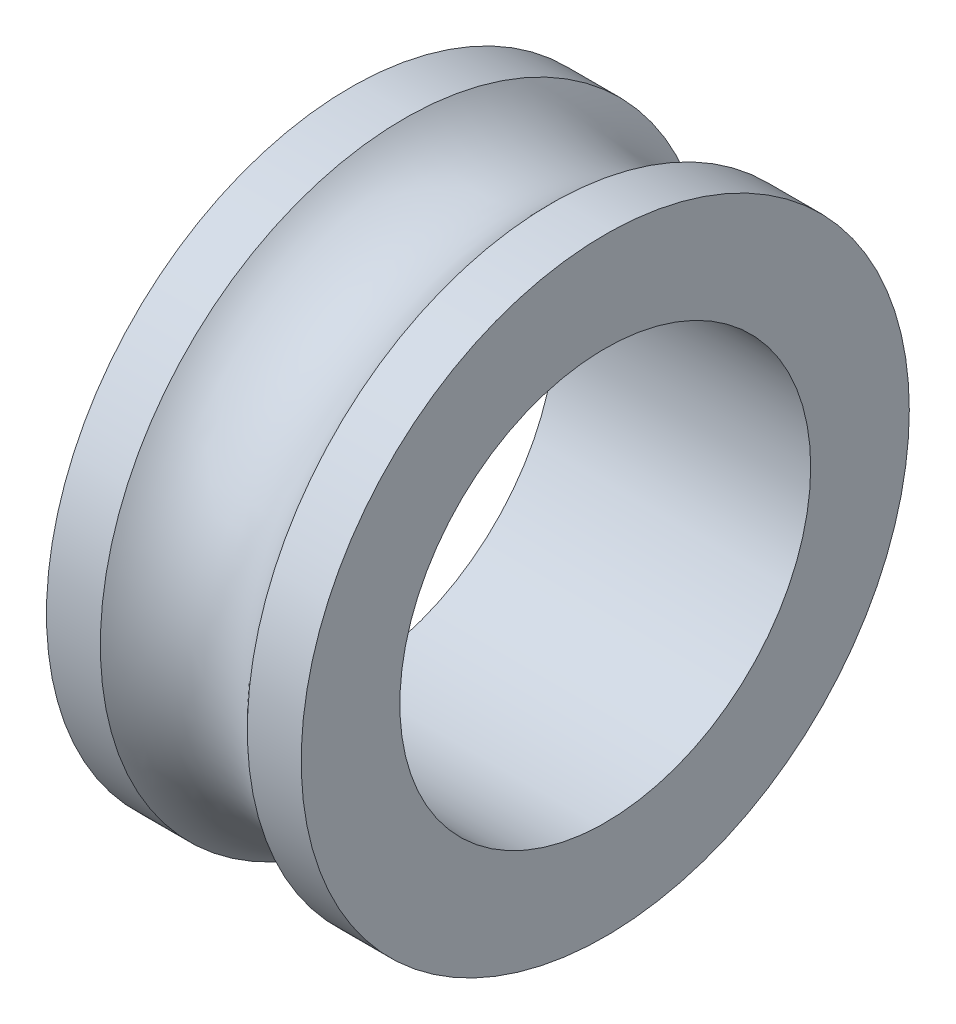
SolidWorks part; units mm, degrees
ref_plane "Front Plane" through (0, 0, 0) normal (0, 0, 1) x (1, 0, 0)
ref_plane "Top Plane" through (0, 0, 0) normal (0, 1, 0) x (1, 0, 0)
ref_plane "Right Plane" through (0, 0, 0) normal (1, 0, 0) x (0, 0, -1)
sketch "Sketch3" plane through (0, 0, 0) normal (0, 0, 1) x (1, 0, 0)
  line L0 (49.7889, 0) -> (0, 0) construction
  line L1 (0, 0) -> (0, 31) construction
  line L2 (0, 37) -> (0, 45) construction
  line L3 (15.5, 37) -> (8.9443, 37)
  line L4 (15.5, 37) -> (15.5, 25)
  line L5 (15.5, 25) -> (-15.5, 25)
  line L6 (-15.5, 37) -> (-15.5, 25)
  line L7 (15.5, 37) -> (-15.5, 25) construction
  line L8 (15.5, 25) -> (-15.5, 37) construction
  line L9 (-8.9443, 37) -> (-15.5, 37)
  arc A0 (-8.9443, 37) -> (8.9443, 37) centre (0, 45) ccw
  dimension "D5" = 12
  dimension "D1" = 37
  dimension "D2" = 25
  dimension "D3" = 31
  dimension "D4" = 8
revolve "Revolve1" add sketch "Sketch3" angle 360 about L0
